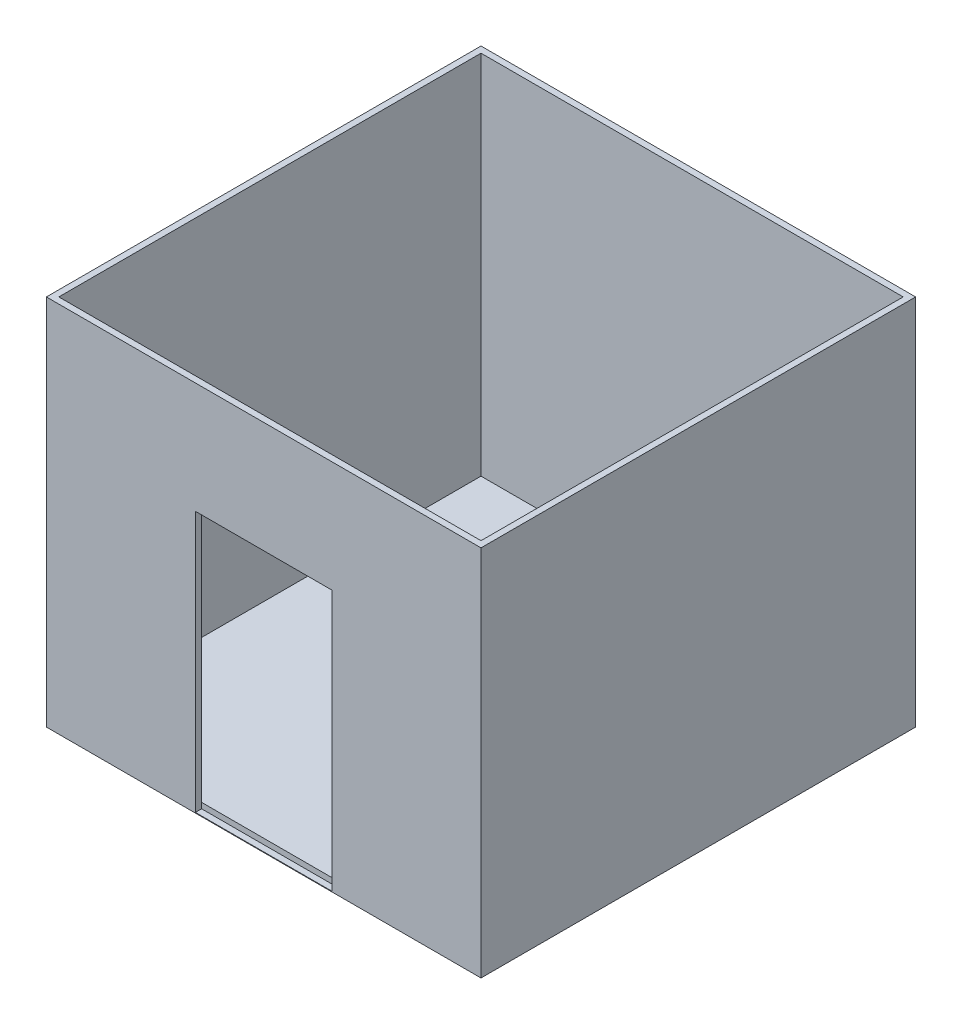
SolidWorks part; units mm, degrees
ref_plane "Front Plane" through (0, 0, 0) normal (0, 0, 1) x (1, 0, 0)
ref_plane "Top Plane" through (0, 0, 0) normal (0, 1, 0) x (1, 0, 0)
ref_plane "Right Plane" through (0, 0, 0) normal (1, 0, 0) x (0, 0, -1)
sketch "Sketch1" plane through (0, 0, 0) normal (0, 1, 0) x (1, 0, 0)
  line L1 (1750, -1750) -> (-1750, -1750)
  line L2 (1750, -1750) -> (1750, 1750)
  line L3 (1750, 1750) -> (-1750, 1750)
  line L4 (-1750, -1750) -> (-1750, 1750)
  line L5 (1750, -1750) -> (-1750, 1750) construction
  line L6 (1750, 1750) -> (-1750, -1750) construction
  point P0 (0, 0)
  dimension "D1" = 3500
  dimension "D2" = 3500
extrude "Boss-Extrude1" add sketch "Sketch1" along normal blind 3000
shell "Shell1" thickness 50
sketch "Sketch2" plane through (0, 0, 1750) normal (0, 0, 1) x (1, 0, 0)
  line L0 (-1750, 0) -> (1750, 0) construction
  line L1 (-550, 2105) -> (550, 2105)
  line L2 (-550, 2105) -> (-550, 5)
  line L3 (-550, 5) -> (550, 5)
  line L4 (550, 2105) -> (550, 5)
  line L5 (-550, 2105) -> (550, 5) construction
  line L6 (-550, 5) -> (550, 2105) construction
  line L7 (0, 0) -> (0, 2933.7611) construction
  point P4 (0, 1055)
  dimension "D1" = 2100
  dimension "D2" = 2105
  dimension "D3" = 1100
extrude "Cut-Extrude1" cut sketch "Sketch2" against normal blind 50
